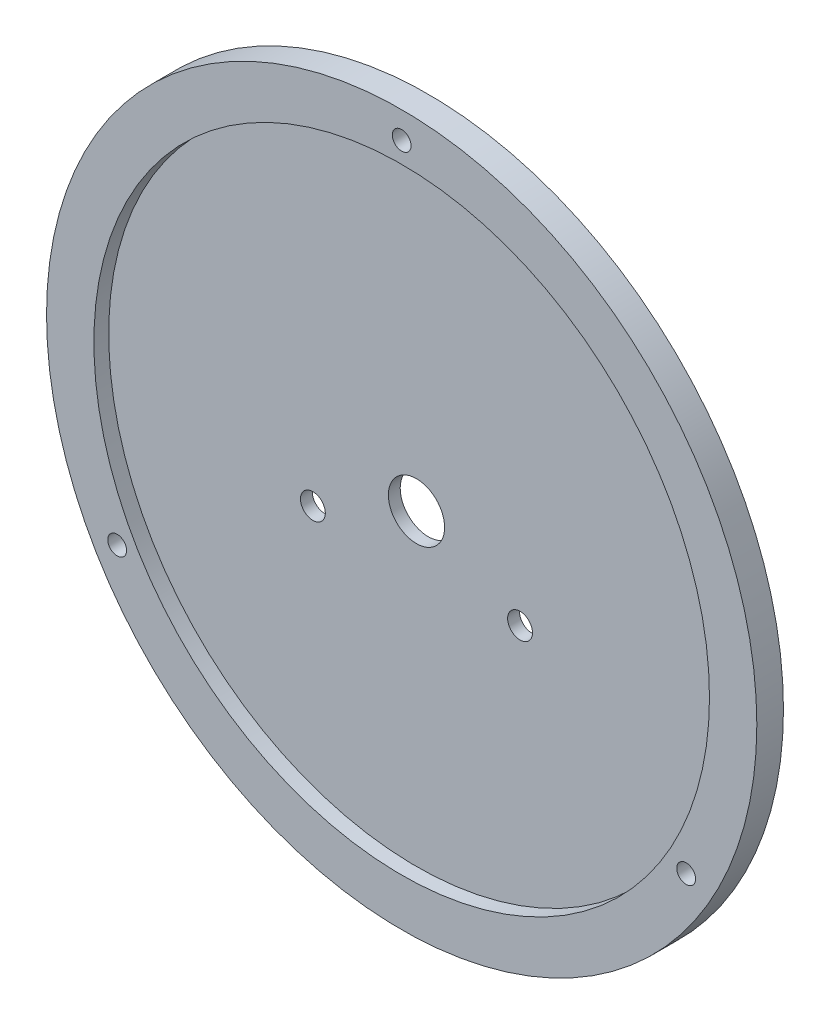
SolidWorks part; units mm, degrees
ref_plane "Alzado" through (0, 0, 0) normal (0, 0, 1) x (1, 0, 0)
ref_plane "Planta" through (0, 0, 0) normal (0, 1, 0) x (1, 0, 0)
ref_plane "Vista lateral" through (0, 0, 0) normal (1, 0, 0) x (0, 0, -1)
sketch "Croquis1" plane through (0, 0, 0) normal (0, 0, 1) x (1, 0, 0)
  circle A0 centre (0, 0) radius 60
  dimension "D1" = 120
extrude "Saliente-Extruir1" add sketch "Croquis1" along normal blind 2
sketch "Croquis2" plane through (0, 0, 2) normal (0, 0, 1) x (1, 0, 0)
  circle A0 centre (0, 0) radius 60
  circle A1 centre (0, 0) radius 52
  dimension "D1" = 8
  dimension "D2" = 120
extrude "Saliente-Extruir2" add sketch "Croquis2" along normal blind 2.5
sketch "Croquis3" plane through (0, 0, 4.5) normal (0, 0, 1) x (1, 0, 0)
  line L0 (0, 0) -> (0, 55.5) construction
  circle A0 centre (0, 55.5) radius 1.5875
  circle A1 centre (48.0644, -27.75) radius 1.5875
  circle A2 centre (-48.0644, -27.75) radius 1.5875
  point P10 (0, 0)
  dimension "D1" = 55.5
  dimension "D2" = 3.175
  dimension "D3" = 3
extrude "Cortar-Extruir1" cut sketch "Croquis3" against normal through all
sketch "Croquis4" plane through (0, 0, 0) normal (0, 0, -1) x (-1, 0, 0)
  circle A0 centre (0, 0) radius 4.75
  dimension "D1" = 9.5
extrude "Cortar-Extruir2" cut sketch "Croquis4" against normal through all
sketch "Croquis5" plane through (0, 0, 0) normal (0, 0, -1) x (-1, 0, 0)
  circle A0 centre (-17.5, -8) radius 2.1
  circle A1 centre (17.5, -8) radius 2.1
extrude "Cortar-Extruir3" cut sketch "Croquis5" against normal through all
